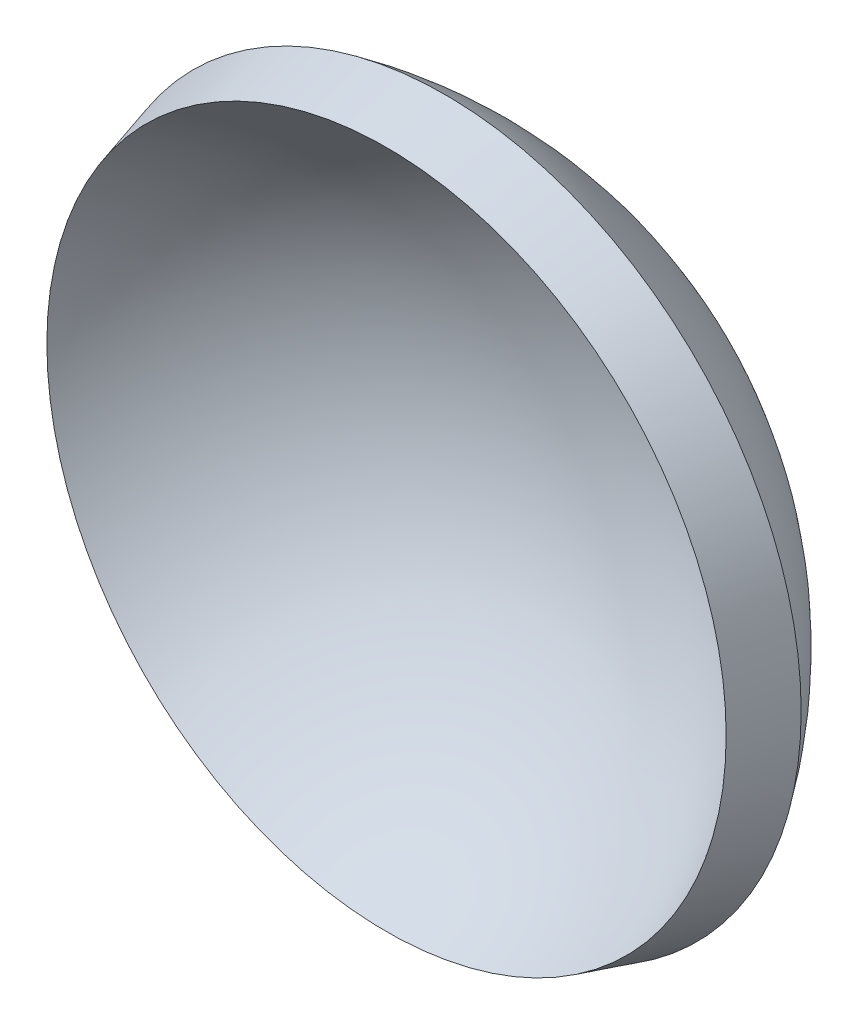
SolidWorks part; units mm, degrees
ref_plane "前视基准面" through (0, 0, 0) normal (0, 0, 1) x (1, 0, 0)
ref_plane "上视基准面" through (0, 0, 0) normal (0, 1, 0) x (1, 0, 0)
ref_plane "右视基准面" through (0, 0, 0) normal (1, 0, 0) x (0, 0, -1)
other "Configuration Table"
sketch "草图2" plane through (0, 0, 0) normal (0, 1, 0) x (1, 0, 0)
  line L0 (0, -24.4018) -> (0, -19.4244) construction
  line L4 (7.155, -28.1601) -> (6.8242, -29.3364)
  line L5 (0, -24.4018) -> (0, -25.2818)
  arc A9 (0, -24.4018) -> (7.155, -28.1601) centre (0, -33.0918) cw
  arc A10 (0, -25.2818) -> (6.8242, -29.3364) centre (0, -33.0521) cw
  point P13 (10.4817, -1.2185)
  point P14 (11.3417, -1.2185)
  dimension "D12" = 0.86
revolve "旋转2" add sketch "草图2" angle 360 about L0
